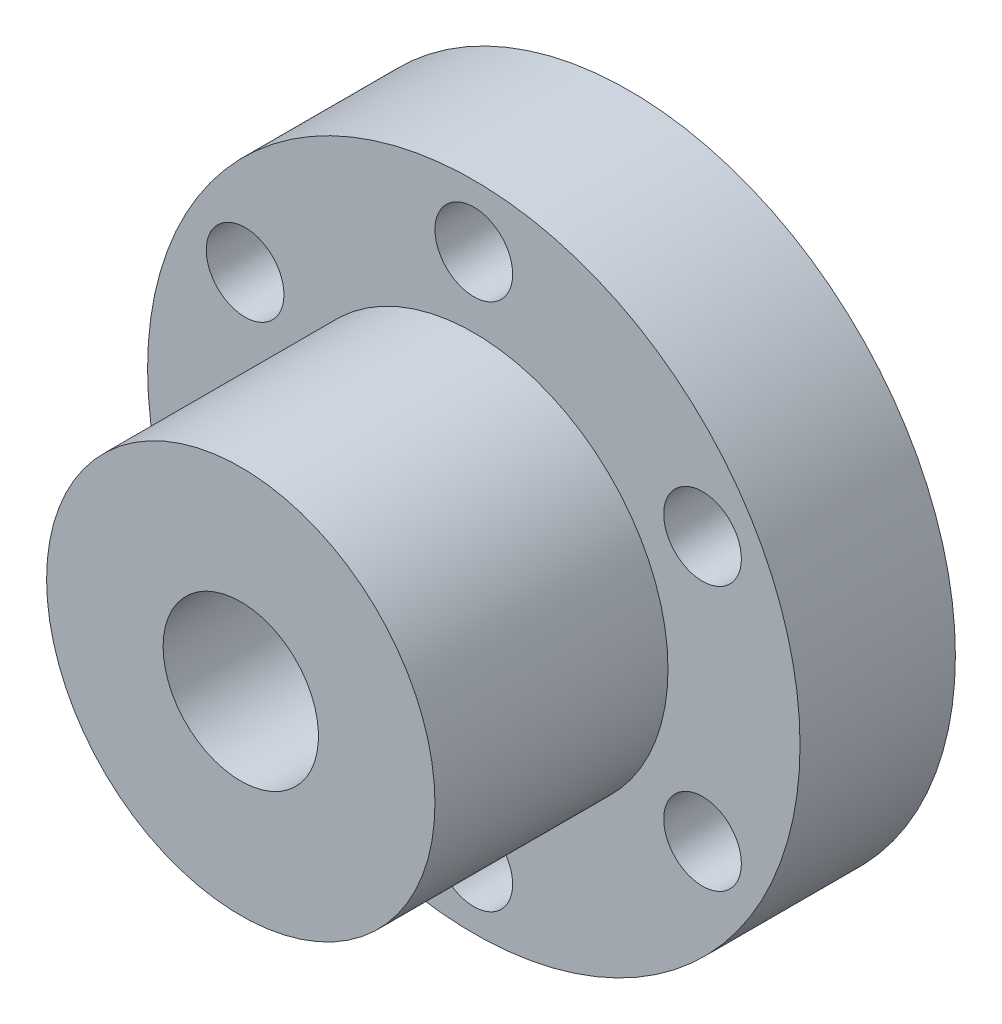
SolidWorks part; units mm, degrees
material "ABS"
ref_plane "Płaszczyzna przednia" through (0, 0, 0) normal (0, 0, 1) x (1, 0, 0)
ref_plane "Płaszczyzna górna" through (0, 0, 0) normal (0, 1, 0) x (1, 0, 0)
ref_plane "Płaszczyzna prawa" through (0, 0, 0) normal (1, 0, 0) x (0, 0, -1)
sketch "Szkic1" plane through (0, 0, 0) normal (0, 0, 1) x (1, 0, 0)
  circle A0 centre (0, 0) radius 21
  dimension "D1" = 42
extrude "Dodanie-wyciągnięcie1" add sketch "Szkic1" along normal blind 10
sketch "Szkic2" plane through (0, 0, 10) normal (0, 0, 1) x (1, 0, 0)
  circle A0 centre (0, 0) radius 12.5
  dimension "D1" = 25
extrude "Dodanie-wyciągnięcie2" add sketch "Szkic2" along normal blind 15
sketch "Szkic3" plane through (0, 0, 10) normal (0, 0, 1) x (1, 0, 0)
  line L0 (0, 0) -> (0, 17) construction
  dimension "D1" = 17
hole_wizard "Otwory ustalające Ø5.0mm1" positions "Szkic4" profile "Szkic5" hole size "Ø5.0" standard "ISO" end condition up to next
sketch "Szkic4" plane through (0, 0, 10) normal (0, 0, 1) x (1, 0, 0)
  point P0 (0, 17)
sketch "Szkic5" plane through (0, 17, 10) normal (1, 0, 0) x (0, -1, 0)
  line L0 (0, 0) -> (0, 10.001)
  line L1 (0, 10.001) -> (2.5, 10.001)
  line L2 (2.5, 10.001) -> (2.5, 0)
  line L5 (2.5, 0) -> (0, 0)
  line L11 (0, -6.35) -> (0, 107.95) construction
  dimension "Średnica otworu na wylot" = 5
  dimension "Głębokość otworu na wylot" = 10.001
pattern_circular "Szyk kołowy1" count 6 over 360 about axis through (0, 0, 0) along (0, 0, 1) of "Otwory ustalające Ø5.0mm1"
sketch "Szkic8" plane through (0, 0, 25) normal (0, 0, 1) x (1, 0, 0)
  circle A0 centre (0, 0) radius 5
  dimension "D1" = 10
extrude "Wytnij-wyciągnięcie1" cut sketch "Szkic8" against normal up to next and the other way through all
